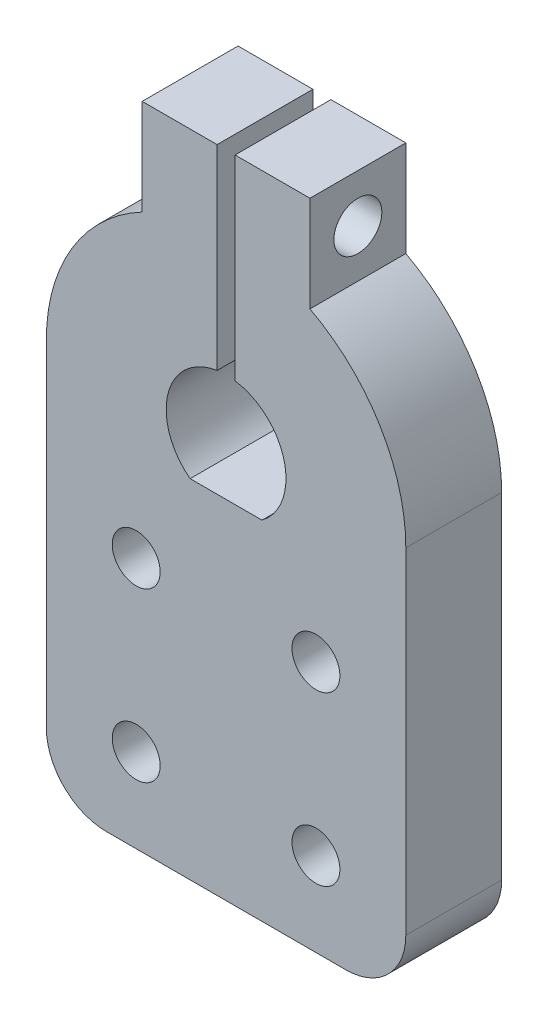
SolidWorks part; units mm, degrees
material "6061 合金"
ref_plane "前视基准面" through (0, 0, 0) normal (0, 0, 1) x (1, 0, 0)
ref_plane "上视基准面" through (0, 0, 0) normal (0, 1, 0) x (1, 0, 0)
ref_plane "右视基准面" through (0, 0, 0) normal (1, 0, 0) x (0, 0, -1)
sketch "草图1" plane through (0, 0, 0) normal (0, 0, 1) x (1, 0, 0)
  line L0 (-15, 0) -> (-15, -33)
  line L1 (-15, -33) -> (15, -33)
  line L2 (15, -33) -> (15, 0)
  line L3 (7, 21.2665) -> (7, 13.2665)
  line L4 (0, -55) -> (0, 55) construction
  line L5 (7, 21.2665) -> (0.75, 21.2665)
  line L6 (0.75, 21.2665) -> (0.75, 4.9434)
  line L7 (-7, 21.2665) -> (-7, 13.2665)
  line L8 (-0.75, 21.2665) -> (-0.75, 4.9434)
  line L9 (-7, 21.2665) -> (-0.75, 21.2665)
  line L11 (3, -4) -> (-3, -4)
  arc A0 (15, 0) -> (7, 13.2665) centre (0, 0) ccw
  arc A1 (-0.75, 4.9434) -> (-3, -4) centre (0, 0) ccw
  arc A2 (-7, 13.2665) -> (-15, 0) centre (0, 0) ccw
  circle A3 centre (-7.5, -12) radius 2
  circle A4 centre (-7.5, -26) radius 2
  circle A5 centre (7.5, -26) radius 2
  circle A6 centre (7.5, -12) radius 2
  arc A7 (3, -4) -> (0.75, 4.9434) centre (0, 0) ccw
  dimension "D1" = 4
  dimension "D3" = 7
  dimension "D2" = 7.5
  dimension "D4" = 14
  dimension "D5" = 33
  dimension "D6" = 12
extrude "凸台-拉伸1" add sketch "草图1" along normal blind 8
sketch "草图2" plane through (7, 0, 0) normal (1, 0, 0) x (0, 0, -1)
  line L0 (-8, 21.2665) -> (0, 21.2665) construction
  circle A0 centre (-4, 17.2665) radius 2
  dimension "D1" = 4
extrude "切除-拉伸1" cut sketch "草图2" against normal blind 15
fillet "圆角2" radius 5 2 edges at (-15, -33, 4) (15, -33, 4)
